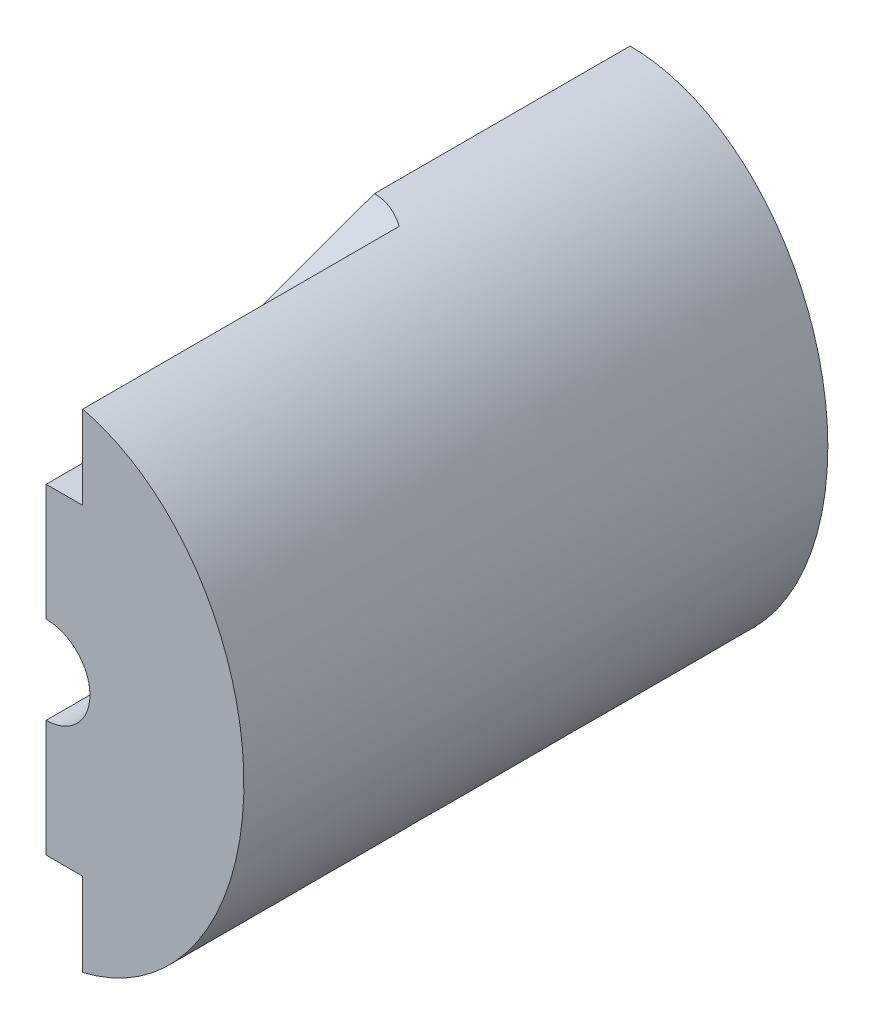
SolidWorks part; units mm, degrees
ref_plane "Alzado" through (0, 0, 0) normal (0, 0, 1) x (1, 0, 0)
ref_plane "Planta" through (0, 0, 0) normal (0, 1, 0) x (1, 0, 0)
ref_plane "Vista lateral" through (0, 0, 0) normal (1, 0, 0) x (0, 0, -1)
sketch "Croquis1" plane through (0, 0, 0) normal (0, 0, 1) x (1, 0, 0)
  ellipse E0 centre (-119.0676, 97.1607) end of major axis (-119.0676, 182.1607) minor radius 67.731
extrude "Saliente-Extruir1" add sketch "Croquis1" along normal blind 200
sketch "Croquis3" plane through (0, 0, 200) normal (0, 0, 1) x (1, 0, 0)
  line L3 (-119.0676, 182.1607) -> (-119.0676, 12.1607) construction
  line L4 (-51.3365, 97.1599) -> (-186.7986, 97.1599) construction
  line L5 (-171.8299, 137.1599) -> (-171.8299, 57.1599)
  line L6 (-171.8299, 137.1599) -> (-178.8306, 137.1599)
  line L7 (-171.8299, 57.1599) -> (-178.8299, 57.1599)
  ellipse E1 centre (-119.0676, 97.1607) end of major axis (-119.0676, 182.1607) minor radius 67.731 construction
  ellipse E2 centre (-119.0676, 97.1607) end of major axis (-119.0676, 182.1607) minor radius 67.731 (-178.8306, 137.1599) -> (-178.8299, 57.1599) ccw
  dimension "D1" = 40
  dimension "D2" = 40
  dimension "D3" = 7
extrude "Cortar-Extruir1" cut sketch "Croquis3" against normal blind 100
sketch "Croquis4" plane through (0, 0, 200) normal (0, 0, 1) x (1, 0, 0)
  line L0 (-178.8306, 137.1599) -> (-171.8299, 137.1599)
  line L1 (-171.8299, 137.1599) -> (-171.8299, 57.1599)
  line L2 (-171.8299, 57.1599) -> (-178.8299, 57.1599)
  ellipse E0 centre (-119.0062, 97.0651) end of major axis (-118.77, 11.9697) minor radius 67.7787 (-178.8306, 137.1599) -> (-178.8299, 57.1599) ccw
  ellipse E1 centre (-119.0676, 97.1607) end of major axis (-119.0676, 182.1607) minor radius 67.731 (-178.8299, 57.1599) -> (-178.8306, 137.1599) ccw construction
extrude "Saliente-Extruir2" add sketch "Croquis4" against normal blind 30
sketch "Croquis5" plane through (0, 0, 0) normal (0, 0, -1) x (-1, 0, 0)
  circle A0 centre (119.0676, 97.1607) radius 7.5
  dimension "D1" = 15
extrude "Saliente-Extruir3" add sketch "Croquis5" along normal blind 30
sketch "Croquis7" plane through (0, 0, 200) normal (0, 0, 1) x (1, 0, 0)
  line L0 (-119.0676, 182.1607) -> (-119.0676, 12.1607) construction
  line L10 (-51.3365, 97.1607) -> (-186.7986, 97.1607) construction
  line L11 (-131.5676, 42.1607) -> (-106.5676, 42.1607)
  line L12 (-131.5676, 42.1607) -> (-131.5676, 13.6208)
  line L14 (-106.5676, 42.1607) -> (-106.5676, 13.6208)
  line L16 (-131.5676, 180.7006) -> (-131.5676, 152.1607)
  line L17 (-131.5676, 152.1607) -> (-106.5676, 152.1607)
  line L18 (-106.5676, 180.7006) -> (-106.5676, 152.1607)
  ellipse E0 centre (-119.0676, 97.1607) end of major axis (-119.0676, 12.1607) minor radius 67.731 (-131.5676, 13.6208) -> (-106.5676, 13.6208) ccw
  ellipse E2 centre (-119.0676, 97.1607) end of major axis (-119.0676, 182.1607) minor radius 67.731 (-178.8299, 57.1599) -> (-178.8306, 137.1599) ccw construction
  ellipse E3 centre (-119.0676, 97.1607) end of major axis (-119.0676, 12.1607) minor radius 67.731 (-106.5676, 180.7006) -> (-131.5676, 180.7006) ccw
  dimension "D1" = 25
  dimension "D2" = 12.5
  dimension "D3" = 30
  dimension "D4" = 25
  dimension "D5" = 12.5
  dimension "D6" = 30
extrude "Cortar-Extruir3" cut sketch "Croquis7" against normal blind 30
sketch "Croquis8" plane through (0, 0, 200) normal (0, 0, 1) x (1, 0, 0)
  line L7 (-119.0676, 202.2019) -> (-197.9563, 202.2019)
  line L8 (-119.0676, 202.2019) -> (-119.0676, 0)
  line L9 (-119.0676, 0) -> (-197.9563, 0)
  line L10 (-197.9563, 202.2019) -> (-197.9563, 0)
extrude "Cortar-Extruir4" cut sketch "Croquis8" against normal through all
sketch "Croquis9" plane through (0, 0, 200) normal (0, 0, 1) x (1, 0, 0)
  line L2 (-119.0676, 42.1607) -> (-119.0676, 152.1607) construction
  line L3 (-106.5676, 42.1607) -> (-119.0676, 42.1607) construction
  line L4 (-119.0676, 152.1607) -> (-106.5676, 152.1607) construction
  circle A1 centre (-119.0676, 97.1607) radius 15
  dimension "D1" = 30
  dimension "D2" = 0
  dimension "D3" = 55
  dimension "D4" = 55
extrude "Cortar-Extruir5" cut sketch "Croquis9" against normal blind 20
sketch "Croquis10" plane through (-106.5676, 0, 0) normal (-1, 0, 0) x (0, 0, 1)
  circle A0 centre (185, 169.6607) radius 7.5
  circle A1 centre (185, 24.6607) radius 7.5
  dimension "D1" = 15
  dimension "D2" = 15
extrude "Cortar-Extruir6" cut sketch "Croquis10" against normal blind 8
sketch "Croquis11" plane through (-119.0676, 0, 0) normal (-1, 0, 0) x (0, 0, 1)
  line L0 (170, 152.1607) -> (81.5451, 184.3557)
  line L1 (81.5451, 184.3557) -> (86.6043, 216.8997)
  line L2 (86.6043, 216.8997) -> (170, 209.0514)
  line L3 (170, 209.0514) -> (170, 152.1607)
  line L4 (170, 42.1607) -> (54.1643, 0)
  line L5 (54.1643, 0) -> (170, 0)
  line L6 (170, 0) -> (170, 42.1607)
  dimension "D1" = 70
  dimension "D2" = 70
extrude "Cortar-Extruir7" cut sketch "Croquis11" against normal blind 12.5
